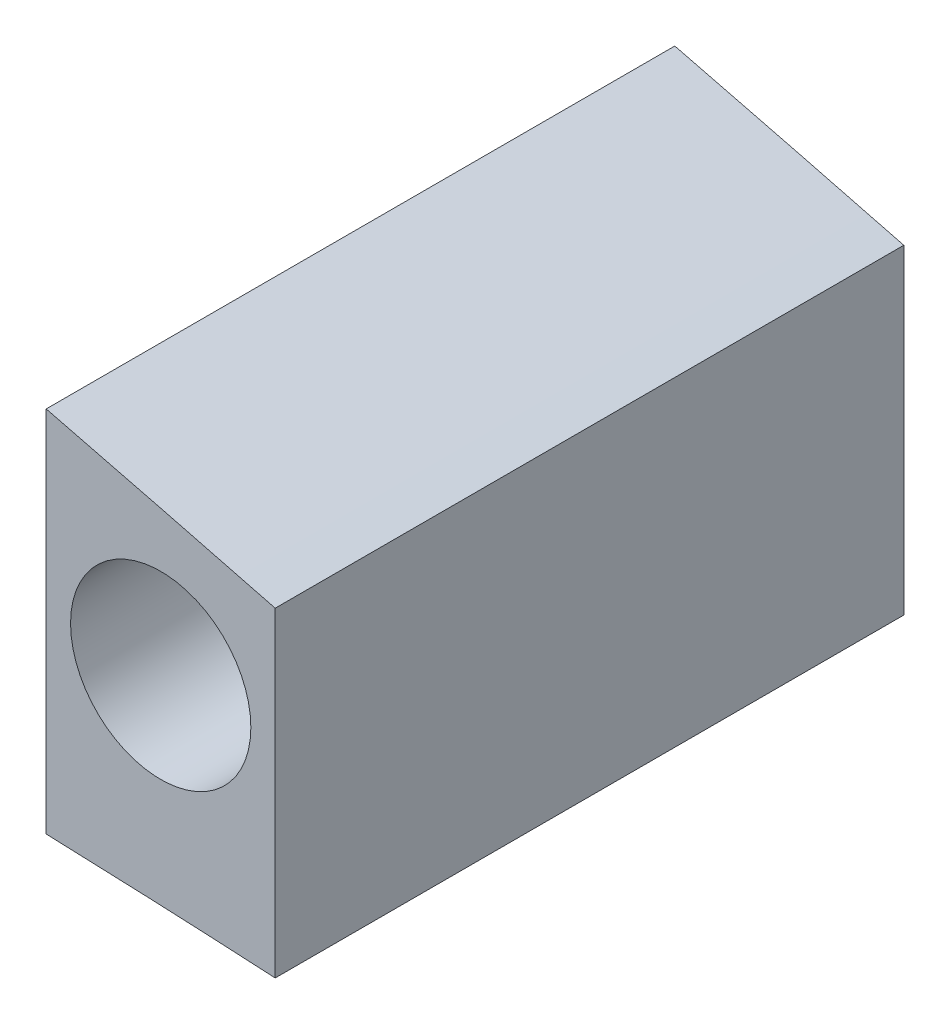
SolidWorks part; units mm, degrees
ref_plane "Front Plane" through (0, 0, 0) normal (0, 0, 1) x (1, 0, 0)
ref_plane "Top Plane" through (0, 0, 0) normal (0, 1, 0) x (1, 0, 0)
ref_plane "Right Plane" through (0, 0, 0) normal (1, 0, 0) x (0, 0, -1)
sketch "Sketch1" plane through (0, 0, 0) normal (0, 0, 1) x (1, 0, 0)
  spline S0 degree 3 poles (0.0006, 0.0001) (0.8106, 7.3592) (8.6491, 17.8566) (26.2867, 29.9752) (52.1111, 42.0692) (89.5976, 49.2908) (131.4008, 47.8848) (173.2567, 40.0411) (217.9611, 29.613) (256.9521, 19.5289) (290.3598, 8.711) (301.2732, 4.3828) (314.8169, -0.5162) (309.8463, 0.0001) knots 0 0 0 0 0.060864 0.113688 0.188609 0.312909 0.448482 0.557612 0.691544 0.852438 0.929756 0.976058 1 1 1 1
  spline S1 degree 3 poles (309.8463, 0.0001) (303.9568, 1.471) (293.9895, 2.094) (276.264, 4.5144) (260.8463, 5.4274) (235.8588, 7.8703) (205.1014, 8.8381) (157.7186, 9.0307) (110.4973, 6.1815) (66.5062, -0.5867) (36.4547, -6.0985) (15.3166, -6.1891) (1.2307, -6.9241) (0.0006, 0.0001) knots 0 0 0 0 0.057787 0.095275 0.171021 0.205339 0.335319 0.464904 0.658702 0.785512 0.893517 0.943092 1 1 1 1
extrude "Boss-Extrude1" add sketch "Sketch1" along normal blind 34.8615
sketch "Sketch2" plane through (0, 0, 34.8615) normal (0, 0, 1) x (1, 0, 0)
  line L1 (372.5284, -56.283) -> (233.6463, -56.283)
  line L2 (372.5284, -56.283) -> (372.5284, 95.9913)
  line L3 (372.5284, 95.9913) -> (233.6463, 95.9913)
  line L4 (233.6463, -56.283) -> (233.6463, 95.9913)
  circle A0 centre (20.32, 10.16) radius 6.35
  circle A1 centre (227.2963, 19.0501) radius 5
  dimension "D2" = 12.7
  dimension "D3" = 10
  dimension "D6" = 20.32
  dimension "D1" = 82.55
  dimension "D4" = 19.05
  dimension "D5" = 10.16
  dimension "D7" = 6.35
extrude "Cut-Extrude1" cut sketch "Sketch2" against normal through all
sketch "Sketch3" plane through (0, 0, 34.8615) normal (0, 0, 1) x (1, 0, 0)
  line L0 (233.6463, 25.4528) -> (233.6463, 7.6905) construction
  line L1 (-72.2426, 88.4657) -> (220.9463, 88.4657)
  line L2 (-72.2426, 88.4657) -> (-72.2426, -49.5056)
  line L3 (-72.2426, -49.5056) -> (220.9463, -49.5056)
  line L4 (220.9463, 88.4657) -> (220.9463, -49.5056)
  dimension "D1" = 12.7
extrude "Cut-Extrude2" cut sketch "Sketch3" against normal through all
